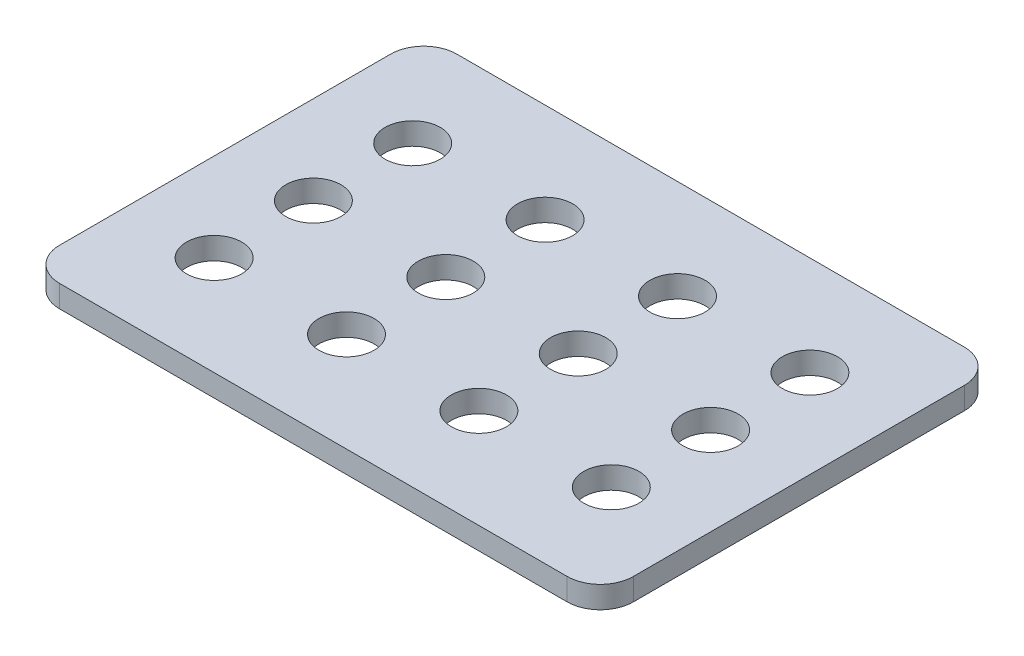
SolidWorks part; units mm, degrees
ref_plane "Front Plane" through (0, 0, 0) normal (0, 0, 1) x (1, 0, 0)
ref_plane "Top Plane" through (0, 0, 0) normal (0, 1, 0) x (1, 0, 0)
ref_plane "Right Plane" through (0, 0, 0) normal (1, 0, 0) x (0, 0, -1)
sketch "Sketch1" plane through (0, 0, 0) normal (0, 1, 0) x (1, 0, 0)
  line L1 (15, 0) -> (245, 0)
  line L2 (0, 15) -> (0, 165)
  line L3 (15, 180) -> (245, 180)
  line L4 (260, 15) -> (260, 165)
  circle A0 centre (40, 135) radius 12.5
  circle A1 centre (100, 135) radius 12.5
  circle A2 centre (160, 135) radius 12.5
  circle A3 centre (220, 135) radius 12.5
  circle A4 centre (100, 90) radius 12.5
  circle A5 centre (160, 90) radius 12.5
  circle A6 centre (220, 90) radius 12.5
  circle A7 centre (100, 45) radius 12.5
  circle A8 centre (160, 45) radius 12.5
  circle A9 centre (220, 45) radius 12.5
  circle A10 centre (40, 90) radius 12.5
  circle A11 centre (40, 45) radius 12.5
  arc A12 (245, 0) -> (260, 15) centre (245, 15) ccw
  arc A13 (245, 180) -> (260, 165) centre (245, 165) cw
  arc A14 (15, 0) -> (0, 15) centre (15, 15) cw
  arc A15 (0, 165) -> (15, 180) centre (15, 165) cw
  point P7 (100, 135)
  point P8 (100, 90)
  point P9 (220, 90)
  point P32 (40, 135)
  point P33 (220, 90)
  point P34 (0, 0)
  point P37 (260, 0)
  point P40 (260, 180)
  point P43 (0, 0)
  point P46 (0, 180)
  dimension "D4" = 25
  dimension "D11" = 15
  dimension "D1" = 180
  dimension "D2" = 260
  dimension "D3" = 45
  dimension "D5" = 40
  dimension "D8" = 60
  dimension "D9" = 45
  dimension "D10" = 45
  dimension "D6" = 4
  dimension "D7" = 3
extrude "Boss-Extrude1" add sketch "Sketch1" along normal blind 10
